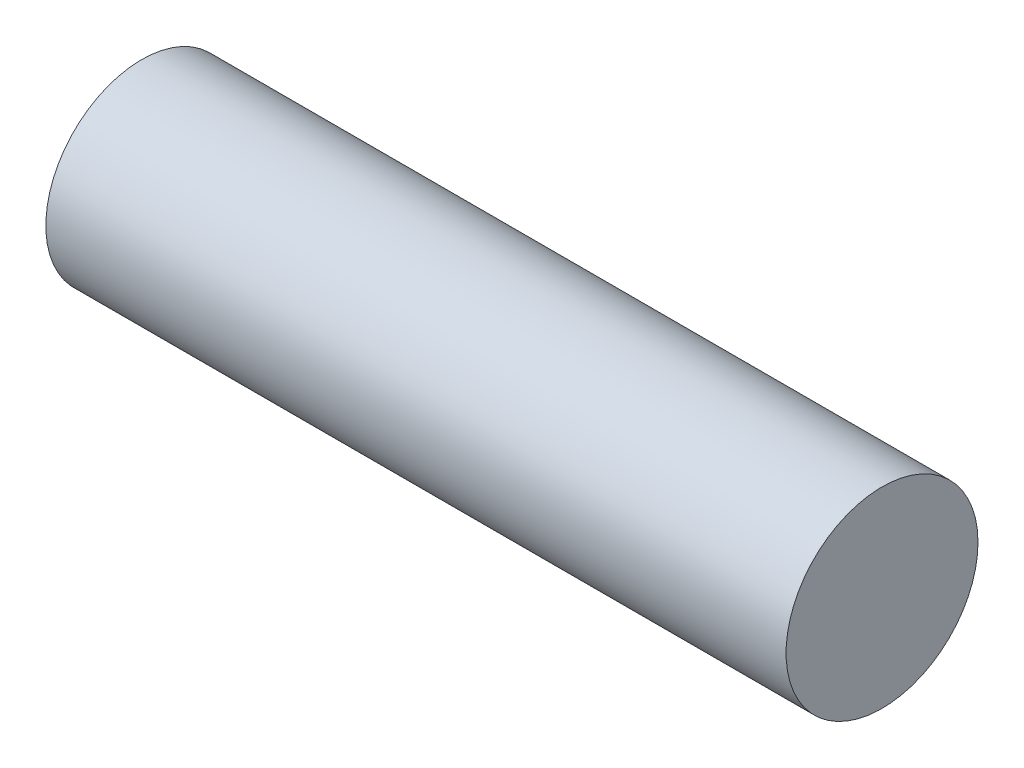
SolidWorks part; units mm, degrees
material "普通碳钢"
ref_plane "前视基准面" through (0, 0, 0) normal (0, 0, 1) x (1, 0, 0)
ref_plane "上视基准面" through (0, 0, 0) normal (0, 1, 0) x (1, 0, 0)
ref_plane "右视基准面" through (0, 0, 0) normal (1, 0, 0) x (0, 0, -1)
sketch "草图1" plane through (0, 0, 0) normal (1, 0, 0) x (0, 0, -1)
  circle A0 centre (0, 0) radius 3.5
  dimension "D1" = 7
extrude "凸台-拉伸1" add sketch "草图1" along normal mid plane 27
